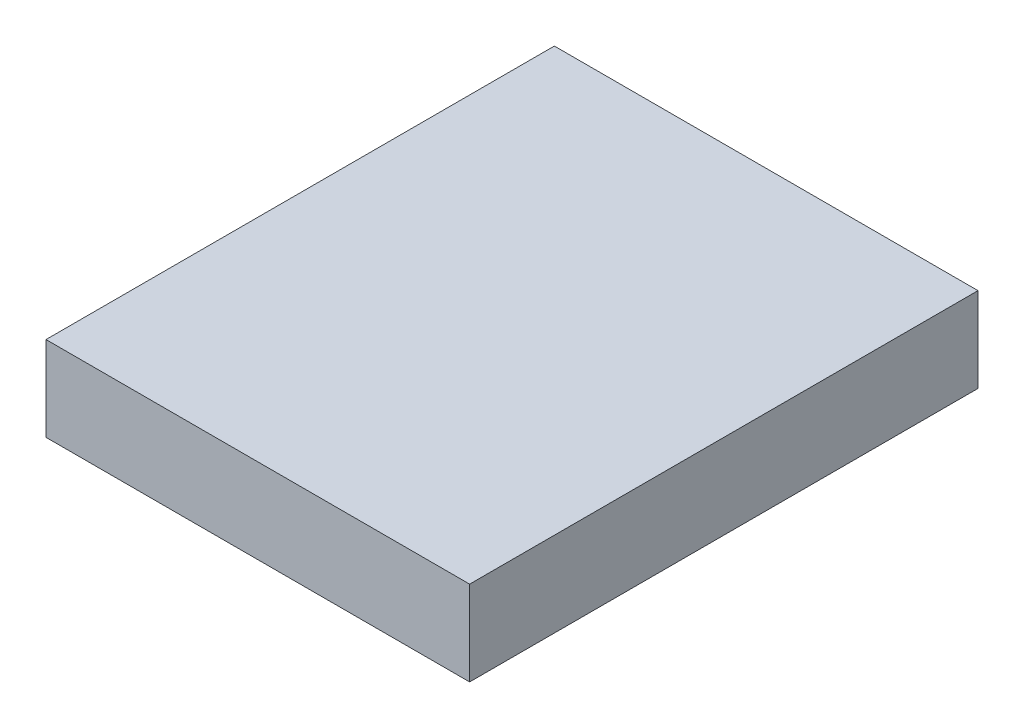
SolidWorks part; units mm, degrees
ref_plane "前视基准面" through (0, 0, 0) normal (0, 0, 1) x (1, 0, 0)
ref_plane "上视基准面" through (0, 0, 0) normal (0, 1, 0) x (1, 0, 0)
ref_plane "右视基准面" through (0, 0, 0) normal (1, 0, 0) x (0, 0, -1)
sketch "草图1" plane through (0, 0, 0) normal (0, 0, 1) x (1, 0, 0)
  line L1 (-50, -10) -> (50, -10)
  line L2 (-50, -10) -> (-50, 10)
  line L3 (-50, 10) -> (50, 10)
  line L4 (50, -10) -> (50, 10)
  line L5 (-50, -10) -> (50, 10) construction
  line L6 (-50, 10) -> (50, -10) construction
  point P0 (0, 0)
extrude "凸台-拉伸1" add sketch "草图1" along normal blind 120
